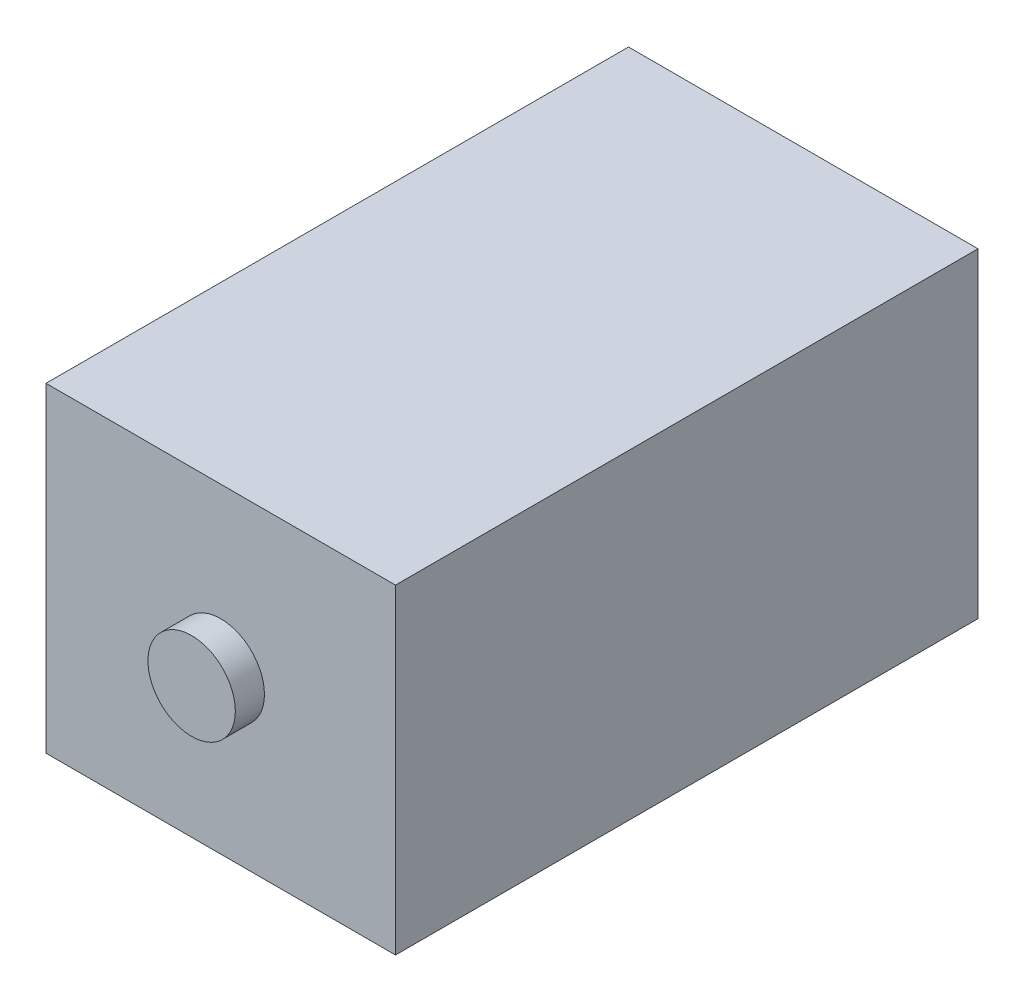
SolidWorks part; units mm, degrees
ref_plane "正面" through (0, 0, 0) normal (0, 0, 1) x (1, 0, 0)
ref_plane "平面" through (0, 0, 0) normal (0, 1, 0) x (1, 0, 0)
ref_plane "右側面" through (0, 0, 0) normal (1, 0, 0) x (0, 0, -1)
sketch "ｽｹｯﾁ1" plane through (0, 0, 0) normal (0, 0, 1) x (1, 0, 0)
  line L1 (6, 5.5) -> (-6, 5.5)
  line L2 (6, 5.5) -> (6, -5.5)
  line L3 (6, -5.5) -> (-6, -5.5)
  line L4 (-6, 5.5) -> (-6, -5.5)
  line L5 (6, 5.5) -> (-6, -5.5) construction
  line L6 (6, -5.5) -> (-6, 5.5) construction
  point P0 (0, 0)
  dimension "D1" = 11
  dimension "D2" = 12
extrude "ﾎﾞｽ - 押し出し1" add sketch "ｽｹｯﾁ1" along normal blind 20
sketch "ｽｹｯﾁ2" plane through (0, 0, 20) normal (0, 0, 1) x (1, 0, 0)
  circle A0 centre (0, 0) radius 1.5
  dimension "D1" = 3
extrude "ﾎﾞｽ - 押し出し2" add sketch "ｽｹｯﾁ2" along normal blind 1
